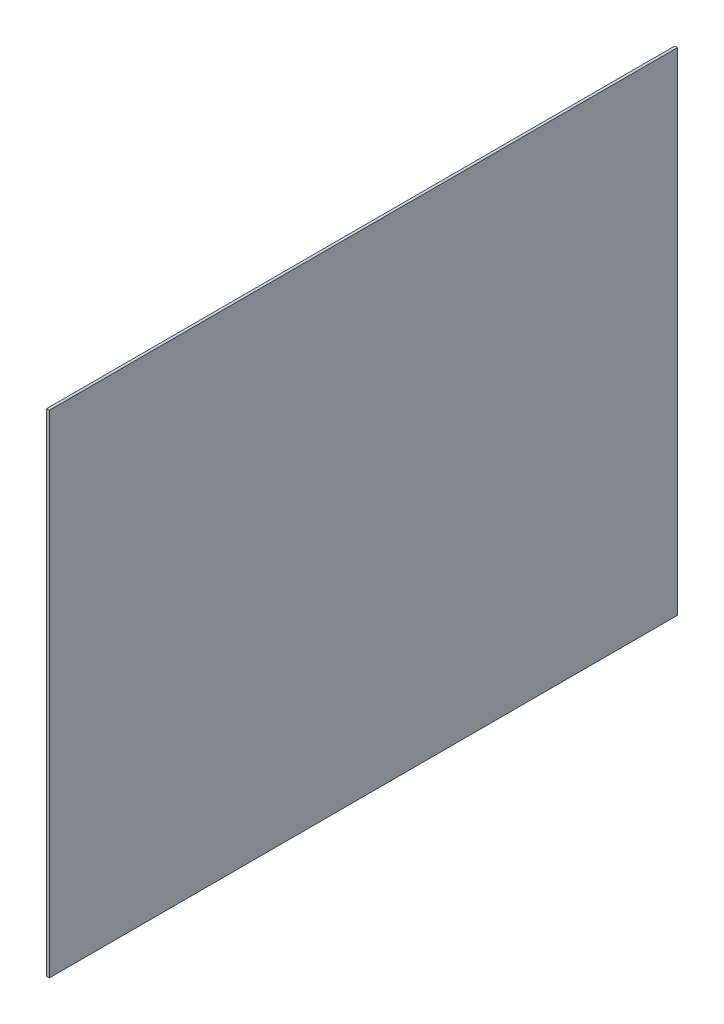
SolidWorks part; units mm, degrees
ref_plane "Front Plane" through (0, 0, 0) normal (0, 0, 1) x (1, 0, 0)
ref_plane "Top Plane" through (0, 0, 0) normal (0, 1, 0) x (1, 0, 0)
ref_plane "Right Plane" through (0, 0, 0) normal (1, 0, 0) x (0, 0, -1)
sketch "Sketch1" plane through (0, 0, 0) normal (1, 0, 0) x (0, 0, -1)
  line L1 (-345, -270) -> (345, -270)
  line L2 (-345, -270) -> (-345, 270)
  line L3 (-345, 270) -> (345, 270)
  line L4 (345, -270) -> (345, 270)
  line L5 (-345, -270) -> (345, 270) construction
  line L6 (-345, 270) -> (345, -270) construction
  point P0 (0, 0)
  dimension "D1" = 690
  dimension "D2" = 540
extrude "Boss-Extrude1" add sketch "Sketch1" along normal blind 3
